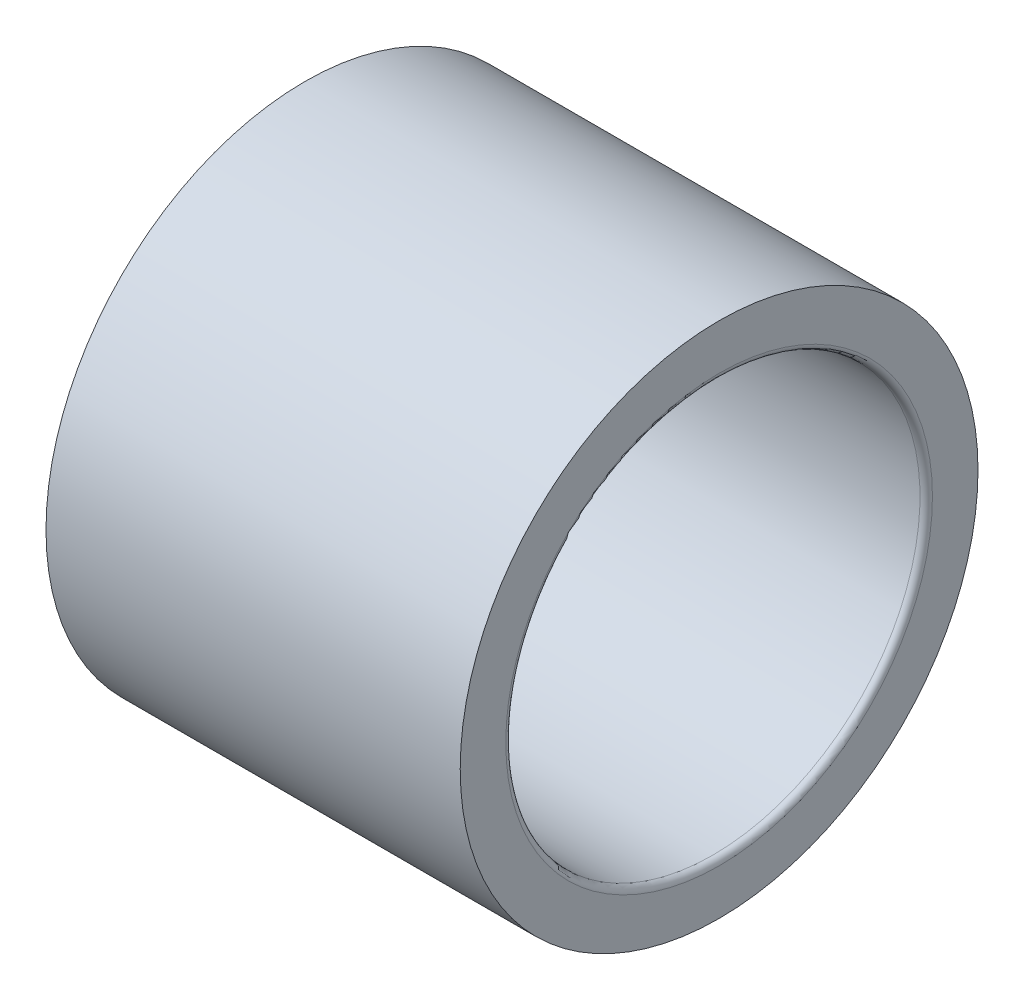
SolidWorks part; units mm, degrees
ref_plane "Front Plane" through (0, 0, 0) normal (0, 0, 1) x (1, 0, 0)
ref_plane "Top Plane" through (0, 0, 0) normal (0, 1, 0) x (1, 0, 0)
ref_plane "Right Plane" through (0, 0, 0) normal (1, 0, 0) x (0, 0, -1)
sketch "Sketch1" plane through (0, 0, 0) normal (0, 0, 1) x (1, 0, 0)
  line L0 (0, 0) -> (20, 0) construction
  line L1 (0.3, 10) -> (19.7, 10)
  line L2 (20, 10.3) -> (20, 12.5)
  line L3 (20, 12.5) -> (0, 12.5)
  line L4 (0, 12.5) -> (0, 10.3)
  arc A0 (0, 10.3) -> (0.3, 10) centre (0.3, 10.3) ccw
  arc A1 (19.7, 10) -> (20, 10.3) centre (19.7, 10.3) ccw
revolve "Revolve1" add sketch "Sketch1" angle 360 about L0
